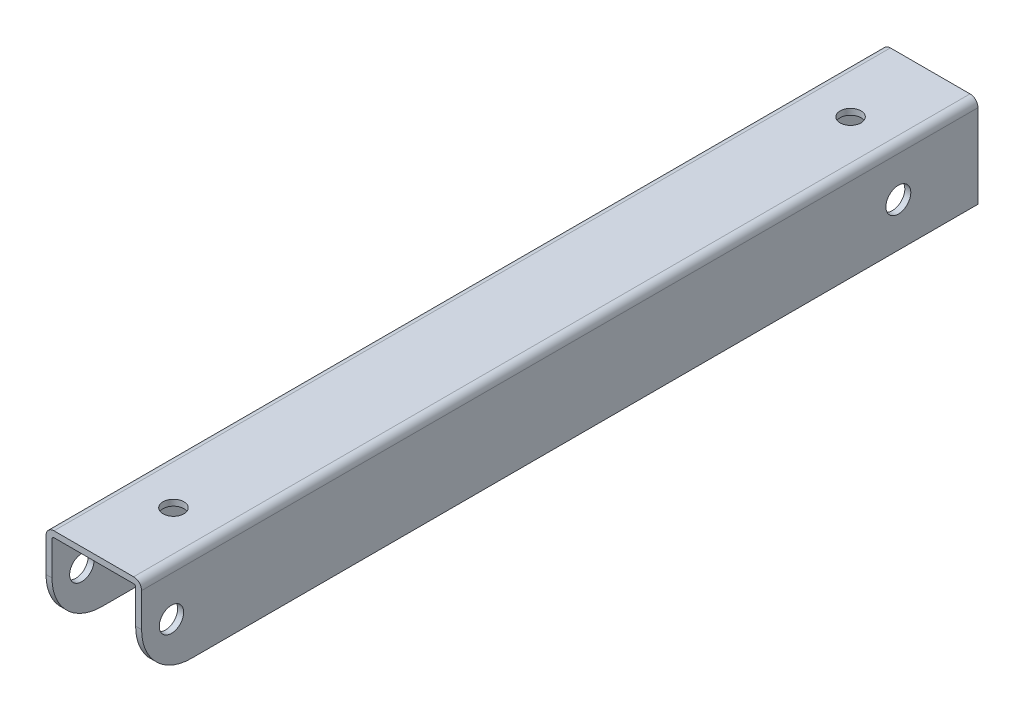
SolidWorks part; units mm, degrees
ref_plane "Ön Düzlem" through (0, 0, 0) normal (0, 0, 1) x (1, 0, 0)
ref_plane "Üst Düzlem" through (0, 0, 0) normal (0, 1, 0) x (1, 0, 0)
ref_plane "Sağ Düzlem" through (0, 0, 0) normal (1, 0, 0) x (0, 0, -1)
sketch "Çizim1" plane through (0, 0, 0) normal (0, 0, 1) x (1, 0, 0)
  line L0 (-37.0446, 41.375) -> (4.9554, 41.375)
  line L1 (4.9554, -1.625) -> (4.9554, 41.375)
  line L2 (-37.0446, 41.375) -> (-37.0446, -1.625)
  dimension "D1" = 43
  dimension "D2" = 43
  dimension "D3" = 42
extrude "Ekstrüzyon-İnce10" add sketch "Çizim1" along normal blind 420 thin thin type one direction wall 3
hole_wizard "M12 Helisarmal için Zıvana matkabı1" positions "Çizim2" profile "Çizim3" size "M12x1.75" standard "ANSI Metrik" slot yes end condition through all
sketch "Çizim2" plane through (-40.0446, 0, 0) normal (-1, 0, 0) x (0, 0, 1)
  line L0 (420, 40.375) -> (0, 40.375) construction
  line L1 (0, 40.375) -> (0, -1.625) construction
  point P0 (40, 20.375)
  dimension "D1" = 20
  dimension "D2" = 40
sketch "Çizim3" plane through (-40.0446, 20.375, 40) normal (0, 1, 0) x (0, 0, 1)
  line L0 (0, 0) -> (0, 48)
  line L1 (0, 48) -> (6.25, 48)
  line L2 (6.25, 48) -> (6.25, 0)
  line L5 (6.25, 0) -> (0, 0)
  line L11 (0, -6.35) -> (0, 107.95) construction
  dimension "Thru Hole Dia." = 12.5
  dimension "Thru Hole Depth" = 48
hole_wizard "M12 Helisarmal için Zıvana matkabı2" positions "Çizim4" profile "Çizim5" size "M12x1.5" standard "ANSI Metrik" slot yes end condition through all
sketch "Çizim4" plane through (-40.0446, 0, 0) normal (-1, 0, 0) x (0, 0, 1)
  line L0 (420, 40.375) -> (0, 40.375) construction
  line L1 (420, 40.375) -> (420, -1.625) construction
  point P0 (405, 20.375)
  dimension "D1" = 20
  dimension "D2" = 15
sketch "Çizim5" plane through (-40.0446, 20.375, 405) normal (0, 1, 0) x (0, 0, 1)
  line L0 (0, 0) -> (0, 48)
  line L1 (0, 48) -> (6.125, 48)
  line L2 (6.125, 48) -> (6.125, 0)
  line L5 (6.125, 0) -> (0, 0)
  line L11 (0, -6.35) -> (0, 107.95) construction
  dimension "Thru Hole Dia." = 12.25
  dimension "Thru Hole Depth" = 48
hole_wizard "M10 Helisarmal için Zıvana matkabı1" positions "3B Çizim1" profile "Çizim6" hole size "M10x1.5" standard "ANSI Metrik" end condition through all
sketch3d "3B Çizim1"
  line L0 (3.9554, 44.375, 420) -> (-36.0446, 44.375, 420) construction
  line L1 (3.9554, 44.375, 420) -> (3.9554, 44.375, 0) construction
  line L2 (3.9554, 44.375, 0) -> (-36.0446, 44.375, 0) construction
  point P0 (-16.0446, 44.375, 380)
  point P2 (-16.0446, 44.375, 40)
  dimension "D1" = 40
  dimension "D2" = 20
  dimension "D3" = 40
  dimension "D4" = 20
sketch "Çizim6" plane through (-16.0446, 44.375, 380) normal (1, 0, 0) x (0, 0, 1)
  line L0 (0, 0) -> (0, 46)
  line L1 (0, 46) -> (5.25, 46)
  line L2 (5.25, 46) -> (5.25, 0)
  line L5 (5.25, 0) -> (0, 0)
  line L11 (0, -6.35) -> (0, 107.95) construction
  dimension "Thru Hole Dia." = 10.5
  dimension "Thru Hole Depth" = 46
fillet "Radyus1" radius 25 1 edges at (-38.5446, -1.625, 420)
fillet "Radyus2" radius 25 1 edges at (6.4554, -1.625, 420)
